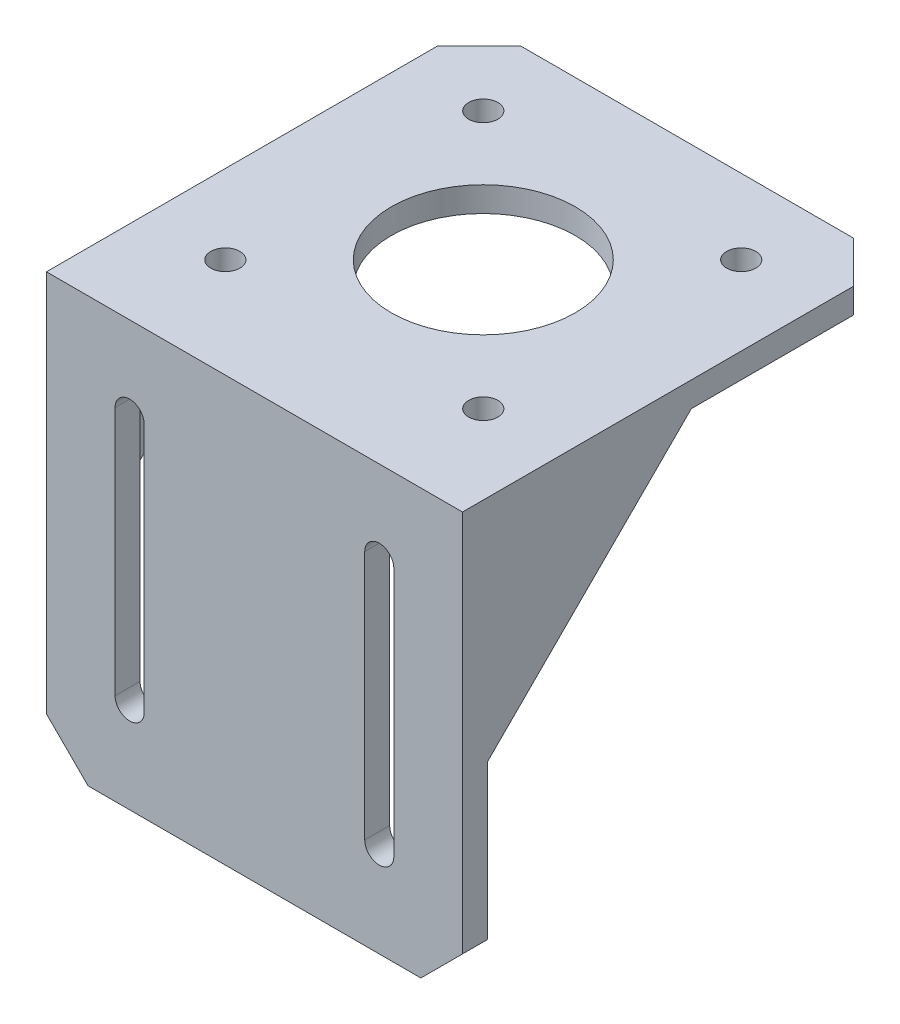
SolidWorks part; units mm, degrees
ref_plane "前视基准面" through (0, 0, 0) normal (0, 0, 1) x (1, 0, 0)
ref_plane "上视基准面" through (0, 0, 0) normal (0, 1, 0) x (1, 0, 0)
ref_plane "右视基准面" through (0, 0, 0) normal (1, 0, 0) x (0, 0, -1)
other "Configuration Table"
sketch "草图1" plane through (0, 0, 0) normal (0, 1, 0) x (1, 0, 0)
  line L0 (-25, 19.5) -> (-20, 24.5)
  line L1 (-25, -24.5) -> (25, -24.5)
  line L2 (-25, -24.5) -> (-25, 19.5)
  line L3 (-20, 24.5) -> (20, 24.5)
  line L4 (25, -24.5) -> (25, 19.5)
  line L5 (-25, -24.5) -> (25, 24.5) construction
  line L6 (-25, 24.5) -> (25, -24.5) construction
  line L7 (20, 24.5) -> (25, 19.5)
  circle A1 centre (0, 0) radius 11.05
  circle A2 centre (15.5, 15.5) radius 1.75
  circle A3 centre (15.5, -15.5) radius 1.75
  circle A4 centre (-15.5, -15.5) radius 1.75
  circle A5 centre (-15.5, 15.5) radius 1.75
  point P0 (0, 0)
  point P23 (0, 0)
  dimension "D3" = 22.1
  dimension "D7" = 15.5
  dimension "D8" = 15.5
  dimension "D9" = 3.5
  dimension "D1" = 50
  dimension "D2" = 49
  dimension "D4" = 24.5
  dimension "D10" = 4
extrude "凸台-拉伸1" add sketch "草图1" along normal blind 3
sketch "草图3" plane through (0, 0, 24.5) normal (0, 0, 1) x (1, 0, 0)
  line L0 (25, 3) -> (25, 0) construction
  line L1 (-25, 3) -> (25, 3)
  line L2 (-25, 3) -> (-25, -43)
  line L3 (-20, -48) -> (20, -48)
  line L4 (25, 3) -> (25, -43)
  line L5 (-25, -43) -> (-20, -48)
  line L6 (20, -48) -> (25, -43)
  line L7 (0, 3) -> (0, -49997) construction
  line L8 (-15, -7) -> (-15, -37) construction
  line L9 (-13.25, -7) -> (-13.25, -37)
  line L10 (-16.75, -7) -> (-16.75, -37)
  line L11 (15, -7) -> (15, -37) construction
  line L12 (13.25, -7) -> (13.25, -37)
  line L13 (16.75, -7) -> (16.75, -37)
  arc A0 (-13.25, -7) -> (-16.75, -7) centre (-15, -7) ccw
  arc A1 (-16.75, -37) -> (-13.25, -37) centre (-15, -37) ccw
  arc A2 (13.25, -7) -> (16.75, -7) centre (15, -7) cw
  arc A3 (16.75, -37) -> (13.25, -37) centre (15, -37) cw
  point P1 (25, -48)
  point P2 (-25, -48)
  point P13 (0, 3)
  point P17 (-15, -22)
  point P24 (15, -22)
  dimension "D2" = 1.75
  dimension "D1" = 51
  dimension "D3" = 15
  dimension "D5" = 30
  dimension "D6" = 10
extrude "凸台-拉伸2" add sketch "草图3" along normal blind 3
sketch "草图4" plane through (25, 0, 0) normal (1, 0, 0) x (0, 0, -1)
  line L0 (-24.5, 0) -> (0, 0)
  line L1 (-24.5, 0) -> (-24.5, -24.5)
  line L2 (-24.5, -43) -> (-24.5, 0) construction
  line L3 (-24.5, -24.5) -> (0, 0)
  dimension "D1" = 24.5
extrude "凸台-拉伸3" add sketch "草图4" against normal blind 3
mirror "镜向1" about plane through (0, 0, 0) normal (1, 0, 0) of "凸台-拉伸3"
